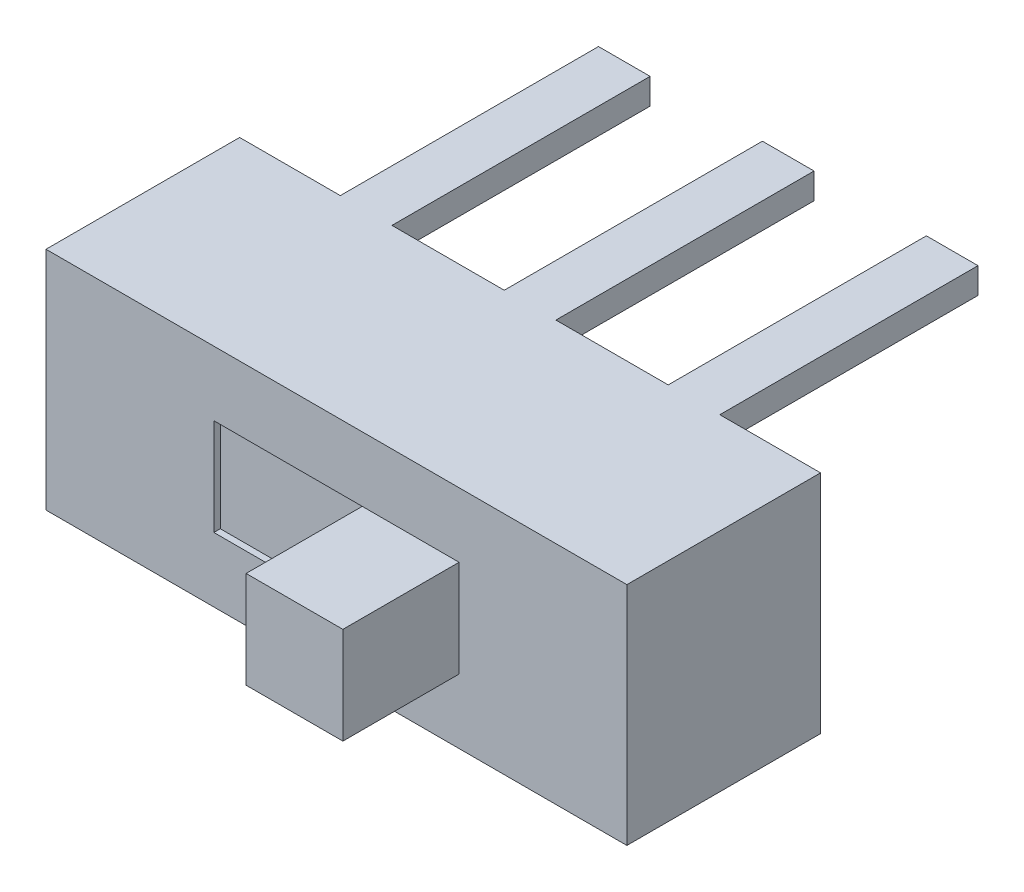
SolidWorks part; units mm, degrees
ref_plane "Спереди" through (0, 0, 0) normal (0, 0, 1) x (1, 0, 0)
ref_plane "Сверху" through (0, 0, 0) normal (0, 1, 0) x (1, 0, 0)
ref_plane "Справа" through (0, 0, 0) normal (1, 0, 0) x (0, 0, -1)
sketch "Эскиз1" plane through (0, 0, 0) normal (0, 1, 0) x (1, 0, 0)
  line L1 (-4.5, 1.5) -> (4.5, 1.5)
  line L2 (-4.5, 1.5) -> (-4.5, -1.5)
  line L3 (-4.5, -1.5) -> (4.5, -1.5)
  line L4 (4.5, 1.5) -> (4.5, -1.5)
  line L5 (-4.5, 1.5) -> (4.5, -1.5) construction
  line L6 (-4.5, -1.5) -> (4.5, 1.5) construction
  point P0 (0, 0)
  dimension "D1" = 9
  dimension "D2" = 3
extrude "Бобышка-Вытянуть1" add sketch "Эскиз1" along normal blind 3.5
sketch "Эскиз2" plane through (0, 0, 1.5) normal (0, 0, 1) x (1, 0, 0)
  line L0 (4.5, 3.5) -> (4.5, 0) construction
  line L1 (-1.9, 2.5) -> (1.9, 2.5)
  line L2 (-1.9, 2.5) -> (-1.9, 1)
  line L3 (-1.9, 1) -> (1.9, 1)
  line L4 (1.9, 2.5) -> (1.9, 1)
  line L5 (-1.9, 2.5) -> (1.9, 1) construction
  line L6 (-1.9, 1) -> (1.9, 2.5) construction
  point P0 (0, 1.75)
  point P8 (4.5, 1.75)
  dimension "D1" = 1.5
  dimension "D2" = 3.8
extrude "Вырез-Вытянуть1" cut sketch "Эскиз2" against normal blind 0.1
sketch "Эскиз3" plane through (0, 0, 1.4) normal (0, 0, 1) x (1, 0, 0)
  line L0 (-1.9, 1) -> (1.9, 1) construction
  line L1 (1.9, 2.5) -> (0.4, 2.5)
  line L2 (1.9, 2.5) -> (1.9, 1)
  line L3 (1.9, 1) -> (0.4, 1)
  line L4 (0.4, 2.5) -> (0.4, 1)
extrude "Бобышка-Вытянуть2" add sketch "Эскиз3" along normal blind 1.9
sketch "Эскиз4" plane through (0, 0, -1.5) normal (0, 0, -1) x (-1, 0, 0)
  line L0 (-4.5, 3.5) -> (4.5, 3.5) construction
  line L1 (-2.94, 3.1) -> (-2.14, 3.1)
  line L2 (-2.94, 3.1) -> (-2.94, 3.5)
  line L3 (-2.94, 3.5) -> (-2.14, 3.5)
  line L4 (-2.14, 3.1) -> (-2.14, 3.5)
  line L5 (-2.94, 3.1) -> (-2.14, 3.5) construction
  line L6 (-2.94, 3.5) -> (-2.14, 3.1) construction
  line L7 (-0.4, 3.1) -> (-0.4, 3.5)
  line L8 (-0.4, 3.1) -> (0.4, 3.1)
  line L9 (0.4, 3.1) -> (0.4, 3.5)
  line L10 (-0.4, 3.5) -> (0.4, 3.5)
  line L11 (-0.4, 3.5) -> (0.4, 3.1) construction
  line L12 (-0.4, 3.1) -> (0.4, 3.5) construction
  line L13 (2.14, 3.1) -> (2.14, 3.5)
  line L14 (2.14, 3.1) -> (2.94, 3.1)
  line L15 (2.94, 3.1) -> (2.94, 3.5)
  line L16 (2.14, 3.5) -> (2.94, 3.5)
  line L17 (2.14, 3.5) -> (2.94, 3.1) construction
  line L18 (2.14, 3.1) -> (2.94, 3.5) construction
  point P0 (-2.54, 3.3)
  point P7 (0, 3.3)
  point P8 (2.54, 3.3)
  dimension "D1" = 0.8
  dimension "D2" = 0.4
  dimension "D4" = 2.54
  dimension "D3" = 3
extrude "Бобышка-Вытянуть3" add sketch "Эскиз4" along normal blind 4
